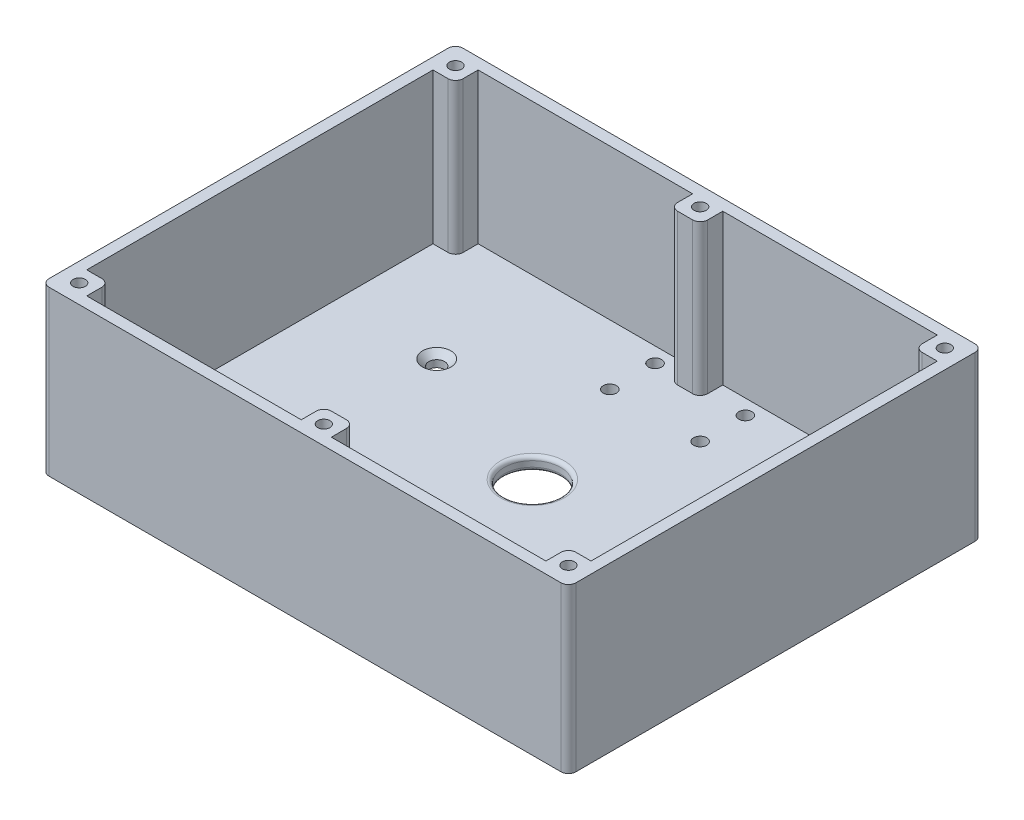
SolidWorks part; units mm, degrees
ref_plane "Front Plane" through (0, 0, 0) normal (0, 0, 1) x (1, 0, 0)
ref_plane "Top Plane" through (0, 0, 0) normal (0, 1, 0) x (1, 0, 0)
ref_plane "Right Plane" through (0, 0, 0) normal (1, 0, 0) x (0, 0, -1)
sketch "Sketch1" plane through (0, 0, 0) normal (0, 1, 0) x (1, 0, 0)
  line L1 (70, -55) -> (-70, -55)
  line L2 (70, -55) -> (70, 55)
  line L3 (70, 55) -> (-70, 55)
  line L4 (-70, -55) -> (-70, 55)
  line L5 (70, -55) -> (-70, 55) construction
  line L6 (70, 55) -> (-70, -55) construction
  point P0 (0, 0)
  dimension "D1" = 110
  dimension "D2" = 140
extrude "Bottom" add sketch "Sketch1" along normal blind 3.5
sketch "Sketch3" plane through (0, 3.5, 0) normal (0, 1, 0) x (1, 0, 0)
  line L0 (-70, 55) -> (70, 55)
  line L1 (70, 55) -> (70, -55)
  line L2 (70, -55) -> (-70, -55)
  line L3 (-70, -55) -> (-70, 55)
  line L4 (-61, 52) -> (-4, 52)
  line L5 (67, 46) -> (67, -46)
  line L6 (61, -52) -> (4, -52)
  line L7 (0, 55) -> (0, -55) construction
  line L8 (-67, 46) -> (-61, 46)
  line L9 (-61, 46) -> (-61, 52)
  line L10 (61, 52) -> (61, 46)
  line L11 (61, 46) -> (67, 46)
  line L12 (67, -46) -> (61, -46)
  line L13 (61, -46) -> (61, -52)
  line L14 (-67, -46) -> (-61, -46)
  line L15 (-61, -46) -> (-61, -52)
  line L16 (-67, -46) -> (-67, 46)
  line L17 (0, 0) -> (67, 0) construction
  line L18 (4, -52) -> (4, -46)
  line L19 (-4, 52) -> (-4, 46)
  line L20 (-4, 46) -> (4, 46)
  line L21 (4, 52) -> (4, 46)
  line L22 (0, 46) -> (0, 42.7097) construction
  line L23 (4, 52) -> (61, 52)
  line L24 (-4, -46) -> (4, -46)
  line L25 (-4, -52) -> (-4, -46)
  line L26 (-4, -52) -> (-61, -52)
  dimension "D1" = 3
  dimension "D2" = 3
  dimension "D3" = 3
  dimension "D4" = 3
  dimension "D5" = 6
  dimension "D6" = 8
extrude "Wall" add sketch "Sketch3" along normal blind 40
sketch "Sketch4" plane through (0, 43.5, 0) normal (0, 1, 0) x (1, 0, 0)
  line L0 (-70, 55) -> (-70, -55) construction
  line L1 (70, 55) -> (-70, 55) construction
  line L2 (70, -55) -> (70, 55) construction
  line L3 (-70, -55) -> (70, -55) construction
  line L4 (0, 55) -> (0, 30.3541) construction
  line L5 (70, 0) -> (33.8613, 0) construction
  circle A0 centre (-65, 50) radius 1.625
  circle A1 centre (65, 50) radius 1.625
  circle A2 centre (65, -50) radius 1.625
  circle A3 centre (-65, -50) radius 1.625
  circle A4 centre (0, 50) radius 1.625
  circle A5 centre (0, -50) radius 1.625
  dimension "D1" = 3.25
  dimension "D4" = 5
  dimension "D2" = 5
  dimension "D3" = 5
  dimension "D5" = 5
extrude "Top Plate Screw Holes" cut sketch "Sketch4" against normal blind 30 draft 1
fillet "Fillet14" radius 2 1 edges at (-4, 23.5, 46)
fillet "Fillet13" radius 2 1 edges at (4, 23.5, 46)
fillet "Fillet12" radius 2 1 edges at (-4, 23.5, -46)
fillet "Fillet11" radius 2 1 edges at (4, 23.5, -46)
fillet "Fillet1" radius 2 1 edges at (-61, 23.5, 46)
fillet "Fillet2" radius 2 1 edges at (61, 23.5, 46)
fillet "Fillet3" radius 2 1 edges at (61, 23.5, -46)
fillet "Fillet4" radius 2 1 edges at (-61, 23.5, -46)
fillet "Fillet5" radius 2 1 edges at (-70, 21.75, -55)
fillet "Fillet6" radius 2 1 edges at (70, 21.75, -55)
fillet "Fillet7" radius 2 1 edges at (70, 21.75, 55)
fillet "Fillet8" radius 2 1 edges at (-70, 21.75, 55)
sketch "M4 Mount" plane through (0, 3.5, 0) normal (0, -1, 0) x (1, 0, 0)
  line L0 (70, 53) -> (70, -53) construction
  line L1 (0, 0) -> (23.8675, 0) construction
  line L2 (0, 0) -> (0, -19.9393) construction
  circle A0 centre (40, -20) radius 2.1
  circle A1 centre (40, 20) radius 2.1
  circle A2 centre (-40, 20) radius 2.1
  circle A3 centre (-40, -20) radius 2.1
  dimension "D1" = 4.2
  dimension "D2" = 30
  dimension "D3" = 20
  dimension "D4" = 20
extrude "M4 Mount Cut" cut sketch "M4 Mount" along normal through all
sketch "M4 Screw Heads" plane through (0, 3.5, 0) normal (0, 1, 0) x (1, 0, 0)
  circle A0 centre (40, -20) radius 3.75
  circle A1 centre (40, 20) radius 3.75
  circle A2 centre (-40, 20) radius 3.75
  circle A3 centre (-40, -20) radius 3.75
  dimension "D1" = 7.5
extrude "Cut-Extrude3" cut sketch "M4 Screw Heads" against normal blind 10 draft 45
sketch "Sketch7" plane through (0, 0, 0) normal (0, -1, 0) x (1, 0, 0)
  line L0 (68, -55) -> (-68, -55) construction
  line L2 (0, -55) -> (0.5731, 13.4899) construction
  circle A0 centre (0.4184, -5) radius 7.5
  dimension "D1" = 15
  dimension "D2" = 50
extrude "USB Cabel Cut" cut sketch "Sketch7" against normal through all
fillet "Fillet9" radius 1 1 edges at (0.4184, 0, -12.5)
fillet "Fillet10" radius 1 1 edges at (0.4184, 3.5, 2.5)
sketch "Sketch8" plane through (0, 3.5, 0) normal (0, 1, 0) x (1, 0, 0)
  line L0 (0, 46) -> (0, 22.3123) construction
  line L1 (2, 46) -> (-2, 46) construction
  line L2 (-4, 52) -> (-61, 52) construction
  circle A0 centre (-10, 48) radius 1.75
  circle A1 centre (-10, 36) radius 1.75
  circle A2 centre (14, 48) radius 1.75
  circle A3 centre (14, 36) radius 1.75
  dimension "D1" = 3.5
  dimension "D5" = 14
  dimension "D2" = 12
  dimension "D3" = 10
  dimension "D4" = 4
extrude "Cut-Extrude4" cut sketch "Sketch8" against normal blind 10
equation "\"BOXWALL\"=3"
equation "\"D1@Sketch3\"=\"BOXWALL\""
equation "\"D2@Sketch3\"=\"BOXWALL\""
equation "\"D3@Sketch3\"=\"BOXWALL\""
equation "\"D4@Sketch3\"=\"BOXWALL\""
equation "\"SCREW_M3\"=3.5"
equation "\"D1@Sketch8\"=\"SCREW_M3\""
